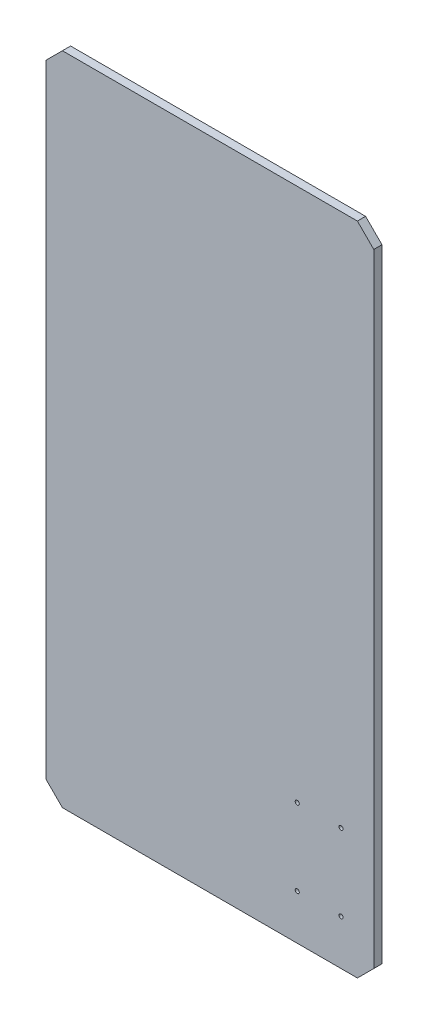
SolidWorks part; units mm, degrees
ref_plane "正面" through (0, 0, 0) normal (0, 0, 1) x (1, 0, 0)
ref_plane "平面" through (0, 0, 0) normal (0, 1, 0) x (1, 0, 0)
ref_plane "右側面" through (0, 0, 0) normal (1, 0, 0) x (0, 0, -1)
sketch "ｽｹｯﾁ1" plane through (0, 0, 0) normal (0, 0, 1) x (1, 0, 0)
  line L0 (0, 0) -> (200, 0)
  line L1 (200, 0) -> (200, 400)
  line L2 (200, 400) -> (0, 400)
  line L3 (0, 400) -> (0, 0)
  dimension "D1" = 200
  dimension "D2" = 400
extrude "ﾎﾞｽ - 押し出し1" add sketch "ｽｹｯﾁ1" along normal blind 5
chamfer "面取り1" distance 10 angle 45 1 edges at (0, 0, 2.5)
chamfer "面取り2" distance 10 angle 45 3 edges at (0, 400, 2.5) (200, 400, 2.5) (200, 0, 2.5)
sketch "ｽｹｯﾁ2" plane through (0, 0, 0) normal (0, 0, -1) x (-1, 0, 0)
  line L0 (-200, 10) -> (-200, 390) construction
  point P0 (-180, 27.5472)
  point P1 (-180, 74.2872)
  point P2 (-153.3, 74.2872)
  point P3 (-153.3, 27.5472)
  point P4 (0, 0)
  dimension "D1" = 46.74
  dimension "D2" = 26.7
  dimension "D3" = 20
  dimension "D4" = 26.7
  dimension "D5" = 46.74
hole_wizard "M3 ねじ穴1" positions "ｽｹｯﾁ3" profile "ｽｹｯﾁ4" tap size "M3" standard "ISO" end condition through all
sketch "ｽｹｯﾁ3" plane through (0, 0, 0) normal (0, 0, -1) x (-1, 0, 0)
  point P0 (-180, 74.2872)
  point P3 (-153.3, 74.2872)
  point P6 (-180, 27.5472)
  point P9 (-153.3, 27.5472)
sketch "ｽｹｯﾁ4" plane through (180, 74.2872, 0) normal (1, 0, 0) x (0, 1, 0)
  line L0 (0, 0) -> (0, 5)
  line L1 (0, 5) -> (1.25, 5)
  line L2 (1.25, 5) -> (1.25, 0.275)
  line L3 (1.25, 0.275) -> (1.525, 0)
  line L5 (1.525, 0) -> (0, 0)
  line L6 (-1.25, 0.275) -> (-1.525, 0) construction
  line L11 (0, -6.35) -> (0, 107.95) construction
  dimension "次ｻｰﾌｪｽまでのねじ下穴ﾄﾞﾘﾙ直径" = 2.5
  dimension "次ｻｰﾌｪｽまでのねじ下穴ﾄﾞﾘﾙの深さ" = 5
  dimension "表面の皿穴の直径" = 3.05
  dimension "表面の皿穴の角度" = 90
cosmetic thread "穴のねじ山1" parameters "D2"=3
cosmetic thread "穴のねじ山2" parameters "D2"=3
cosmetic thread "穴のねじ山3" parameters "D2"=3
cosmetic thread "穴のねじ山4" parameters "D2"=3
sketch "ｽｹｯﾁ5" plane through (0, 0, 0) normal (0, 0, -1) x (-1, 0, 0)
  text T0 "Tekitou Na Ita " font "UD デジタル 教科書体 NP-B" height 12
extrude "ｶｯﾄ - 押し出し1" cut sketch "ｽｹｯﾁ5" against normal blind 2
